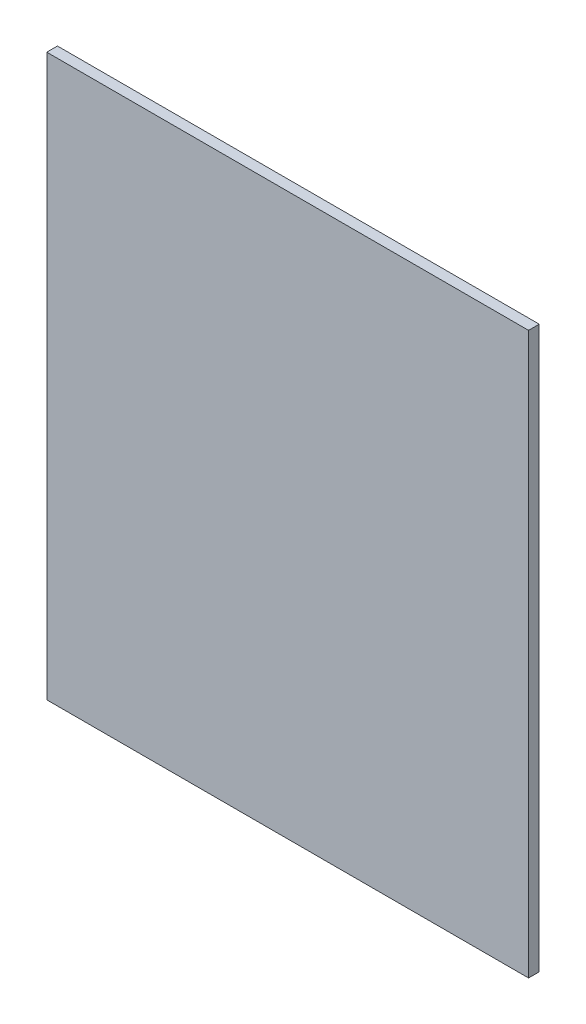
SolidWorks part; units mm, degrees
ref_plane "Front Plane" through (0, 0, 0) normal (0, 0, 1) x (1, 0, 0)
ref_plane "Top Plane" through (0, 0, 0) normal (0, 1, 0) x (1, 0, 0)
ref_plane "Right Plane" through (0, 0, 0) normal (1, 0, 0) x (0, 0, -1)
sketch "Sketch1" plane through (0, 0, 0) normal (0, 0, 1) x (1, 0, 0)
  line L1 (-429.5, -500) -> (429.5, -500)
  line L2 (-429.5, -500) -> (-429.5, 500)
  line L3 (-429.5, 500) -> (429.5, 500)
  line L4 (429.5, -500) -> (429.5, 500)
  line L5 (0, 500) -> (0, -500) construction
  line L6 (-429.5, 0) -> (429.5, 0) construction
  point P0 (0, 0)
  dimension "D1" = 859
  dimension "D2" = 1000
extrude "Boss-Extrude1" add sketch "Sketch1" along normal blind 19.05
sketch "Sketch2" plane through (0, 0, 0) normal (0, 0, -1) x (-1, 0, 0)
  line L0 (-429.5, -500) -> (-429.5, 500) construction
  line L1 (-387.0487, 273.5465) -> (372, 273.5465) construction
  line L2 (-387.0487, 273.5465) -> (-387.0487, -474.125) construction
  line L3 (-387.0487, -474.125) -> (372, -474.125) construction
  line L4 (372, 273.5465) -> (372, -474.125) construction
  line L5 (-7.5243, -474.125) -> (-7.5243, 273.5465) construction
  line L6 (-387.0487, -100.2892) -> (372, -100.2892) construction
  line L7 (-429.5, 500) -> (429.5, 500) construction
  line L8 (-387.0487, 298.9465) -> (372, 298.9465)
  line L9 (397.4, 273.5465) -> (397.4, -474.125)
  line L10 (-387.0487, -499.525) -> (372, -499.525)
  line L11 (-412.4487, 273.5465) -> (-412.4487, -474.125)
  line L12 (-412.4487, -499.525) -> (397.4, -499.525) construction
  line L13 (-412.4487, 298.9465) -> (-412.4487, -499.525) construction
  line L14 (397.4, 298.9465) -> (397.4, -499.525) construction
  line L15 (-412.4487, 298.9465) -> (397.4, 298.9465) construction
  arc A0 (-387.0487, -499.525) -> (-412.4487, -474.125) centre (-387.0487, -474.125) cw
  arc A1 (397.4, -474.125) -> (372, -499.525) centre (372, -474.125) cw
  arc A2 (372, 298.9465) -> (397.4, 273.5465) centre (372, 273.5465) cw
  arc A3 (-387.0487, 298.9465) -> (-412.4487, 273.5465) centre (-387.0487, 273.5465) ccw
  point P208 (-7.5243, -100.2892)
  dimension "D6" = 25.4
  dimension "D1" = 42.4513
  dimension "D2" = 226.4535
  dimension "D3" = 759.0487
  dimension "D4" = 747.6715
  dimension "D5" = 25.4
extrude "Cut-Extrude1" [suppressed] cut sketch "Sketch2" against normal blind 0.5
